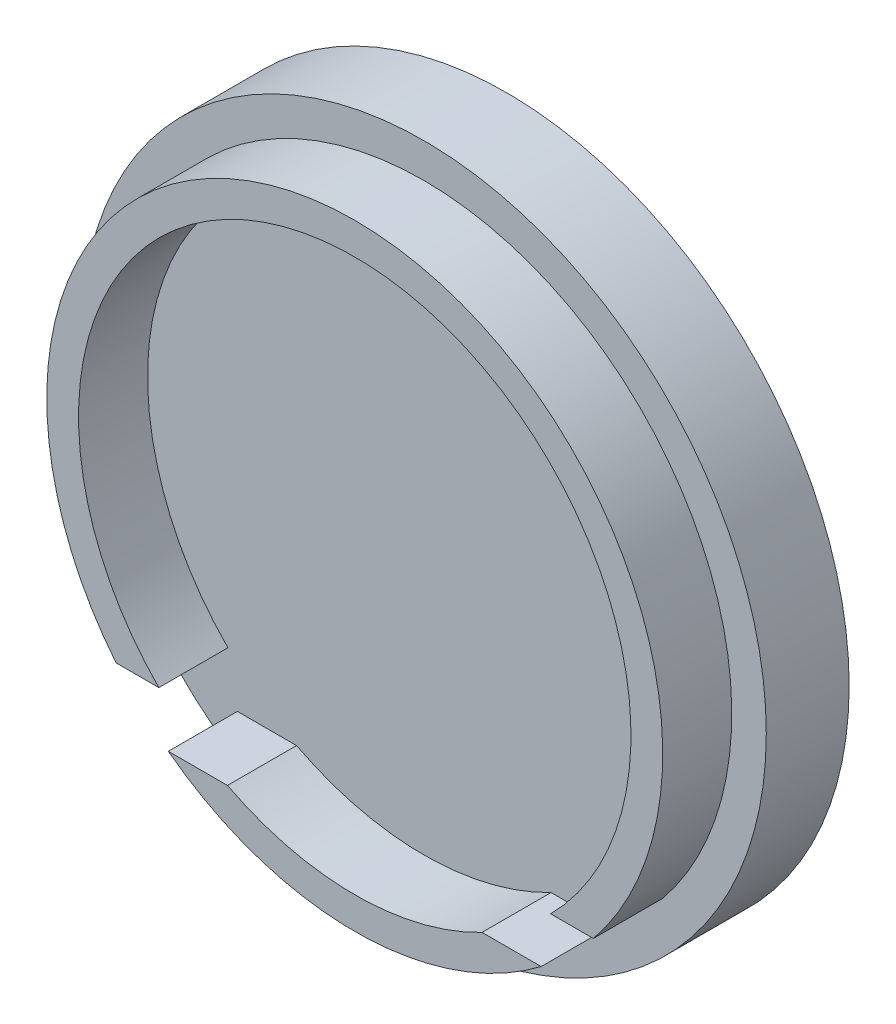
SolidWorks part; units mm, degrees
ref_plane "Front Plane" through (0, 0, 0) normal (0, 0, 1) x (1, 0, 0)
ref_plane "Top Plane" through (0, 0, 0) normal (0, 1, 0) x (1, 0, 0)
ref_plane "Right Plane" through (0, 0, 0) normal (1, 0, 0) x (0, 0, -1)
sketch "Sketch1" plane through (0, 0, 0) normal (0, 0, 1) x (1, 0, 0)
  circle A0 centre (0, 0) radius 24.8
extrude "Boss-Extrude1" add sketch "Sketch1" along normal blind 6
sketch "Sketch2" plane through (0, 0, 6) normal (0, 0, 1) x (1, 0, 0)
  circle A0 centre (0, 0) radius 22.3
  circle A1 centre (0, 0) radius 20
extrude "Boss-Extrude2" add sketch "Sketch2" along normal blind 5
sketch "Sketch3" plane through (0, 0, 11) normal (0, 0, 1) x (1, 0, 0)
  line L1 (14.1841, -14.1) -> (17.2766, -14.1)
  line L2 (17.2766, -14.1) -> (14.1841, -14.1)
  line L4 (9.2162, -17.75) -> (13.4992, -17.75)
  line L5 (13.4992, -17.75) -> (9.2162, -17.75)
  line L6 (-14.1841, -14.1) -> (-17.2766, -14.1)
  line L7 (-9.2162, -17.75) -> (-13.4992, -17.75)
  circle A1 centre (0, 0) radius 22.3 construction
  arc A2 (-17.2766, -14.1) -> (-13.4992, -17.75) centre (0, 0) ccw
  circle A3 centre (0, 0) radius 20 construction
  arc A4 (-14.1841, -14.1) -> (-9.2162, -17.75) centre (0, 0) ccw
  arc A5 (9.2162, -17.75) -> (14.1841, -14.1) centre (0, 0) ccw
  arc A6 (13.4992, -17.75) -> (17.2766, -14.1) centre (0, 0) ccw
  circle M5 centre (0, 0) radius 22.3
  circle M6 centre (0, 0) radius 20
extrude "Cut-Extrude1" cut sketch "Sketch3" against normal blind 5 contours L7 L6 M6 M5 | L4 L1 M6 M5
